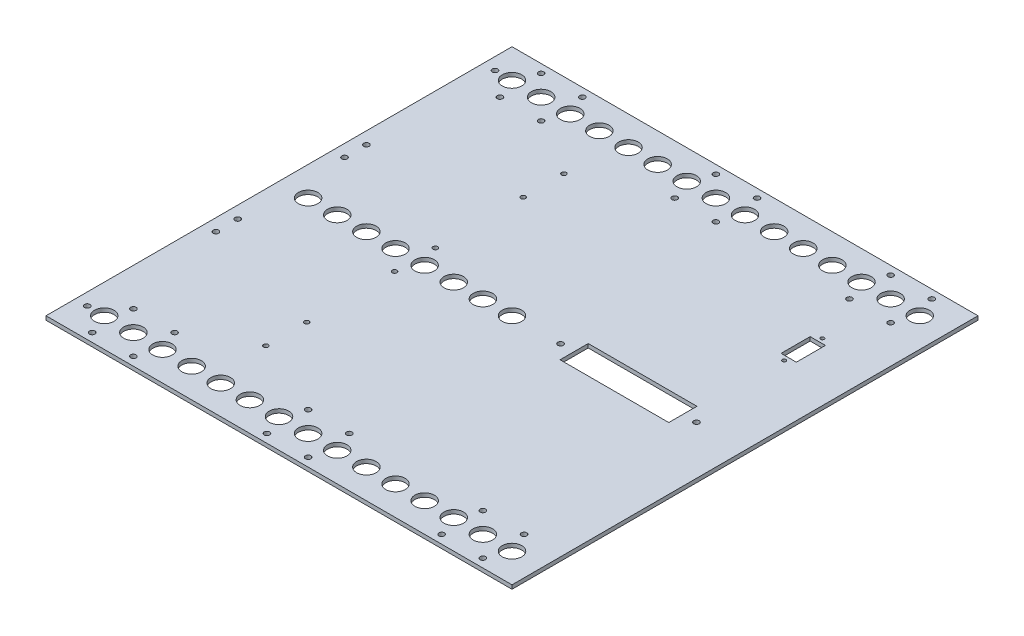
SolidWorks part; units mm, degrees
ref_plane "Front Plane" through (0, 0, 0) normal (0, 0, 1) x (1, 0, 0)
ref_plane "Top Plane" through (0, 0, 0) normal (0, 1, 0) x (1, 0, 0)
ref_plane "Right Plane" through (0, 0, 0) normal (1, 0, 0) x (0, 0, -1)
sketch "Sketch1" plane through (0, 0, 0) normal (0, 1, 0) x (1, 0, 0)
  line L0 (153.4074, 0) -> (-151.3926, 0) construction
  line L1 (-95.25, 133.35) -> (-25.4127, 133.35) construction
  line L2 (-133.35, -133.35) -> (-97.9889, -133.35) construction
  line L3 (-152.4, 42.8625) -> (-136.525, 26.9875) construction
  line L4 (-152.4, 26.9875) -> (-136.525, 42.8625) construction
  line L5 (-152.4, 125.4125) -> (-136.525, 141.2875) construction
  line L6 (-152.4, 141.2875) -> (-136.525, 125.4125) construction
  line L7 (-152.4, 84.1375) -> (-63.5, 84.1375) construction
  line L8 (-63.5, 70.8025) -> (-63.5, 97.4725) construction
  line L9 (-152.4, 141.2875) -> (-152.4, 125.4125) construction
  line L10 (-152.4, 141.2875) -> (-136.525, 141.2875) construction
  line L11 (-136.525, 141.2875) -> (-136.525, 125.4125) construction
  line L12 (-136.525, 125.4125) -> (-12.7, 125.4125) construction
  line L13 (-12.7, 125.4125) -> (-12.7, 42.8625) construction
  line L14 (-12.7, 42.8625) -> (-136.525, 42.8625) construction
  line L15 (-136.525, 42.8625) -> (-136.525, 26.9875) construction
  line L16 (-136.525, 26.9875) -> (-152.4, 26.9875) construction
  line L17 (-152.4, 26.9875) -> (-152.4, 42.8625) construction
  line L18 (-152.4, 125.4125) -> (-152.4, 42.8625) construction
  line L19 (-152.4, -41.275) -> (-136.525, -57.15) construction
  line L20 (-152.4, -152.4) -> (152.4, -152.4)
  line L21 (-152.4, -152.4) -> (-152.4, 152.4)
  line L22 (-152.4, 152.4) -> (152.4, 152.4)
  line L23 (152.4, -152.4) -> (152.4, 152.4)
  line L24 (-152.4, -152.4) -> (152.4, 152.4) construction
  line L25 (-152.4, 152.4) -> (152.4, -152.4) construction
  line L26 (-152.4, -57.15) -> (-136.525, -41.275) construction
  line L27 (-152.4, 41.275) -> (-136.525, 57.15) construction
  line L28 (-152.4, 57.15) -> (-136.525, 41.275) construction
  line L29 (-152.4, 0) -> (-63.5, 0) construction
  line L30 (-63.5, -13.335) -> (-63.5, 13.335) construction
  line L31 (-152.4, 57.15) -> (-152.4, 41.275) construction
  line L32 (-152.4, 57.15) -> (-136.525, 57.15) construction
  line L33 (-136.525, 57.15) -> (-136.525, 41.275) construction
  line L34 (-136.525, 41.275) -> (-12.7, 41.275) construction
  line L35 (-12.7, 41.275) -> (-12.7, -41.275) construction
  line L36 (-12.7, -41.275) -> (-136.525, -41.275) construction
  line L37 (-136.525, -41.275) -> (-136.525, -57.15) construction
  line L38 (-136.525, -57.15) -> (-152.4, -57.15) construction
  line L39 (-152.4, -57.15) -> (-152.4, -41.275) construction
  line L40 (-152.4, 41.275) -> (-152.4, -41.275) construction
  line L41 (-152.4, -125.4125) -> (-136.525, -141.2875) construction
  line L42 (-152.4, -141.2875) -> (-136.525, -125.4125) construction
  line L43 (-152.4, -42.8625) -> (-136.525, -26.9875) construction
  line L44 (-152.4, -26.9875) -> (-136.525, -42.8625) construction
  line L45 (-152.4, -84.1375) -> (-63.5, -84.1375) construction
  line L46 (-63.5, -97.4725) -> (-63.5, -70.8025) construction
  line L47 (-152.4, -26.9875) -> (-152.4, -42.8625) construction
  line L48 (-152.4, -26.9875) -> (-136.525, -26.9875) construction
  line L49 (-136.525, -26.9875) -> (-136.525, -42.8625) construction
  line L50 (-136.525, -42.8625) -> (-12.7, -42.8625) construction
  line L51 (-12.7, -42.8625) -> (-12.7, -125.4125) construction
  line L52 (-12.7, -125.4125) -> (-136.525, -125.4125) construction
  line L53 (-136.525, -125.4125) -> (-136.525, -141.2875) construction
  line L54 (-136.525, -141.2875) -> (-152.4, -141.2875) construction
  line L55 (-152.4, -141.2875) -> (-152.4, -125.4125) construction
  line L56 (-152.4, -42.8625) -> (-152.4, -125.4125) construction
  line L57 (109.3, 66.7) -> (119.3, 85.7) construction
  line L58 (109.3, 85.7) -> (119.3, 85.7)
  line L59 (109.3, 85.7) -> (109.3, 66.7)
  line L60 (109.3, 66.7) -> (119.3, 66.7)
  line L61 (119.3, 85.7) -> (119.3, 66.7)
  line L62 (109.3, 85.7) -> (119.3, 66.7) construction
  line L63 (114.3, 63.7) -> (114.3, 88.7) construction
  line L64 (19.05, -34.925) -> (133.35, 34.925) construction
  line L65 (19.05, 34.925) -> (133.35, 34.925) construction
  line L66 (19.05, 34.925) -> (19.05, -34.925) construction
  line L67 (19.05, -34.925) -> (133.35, -34.925) construction
  line L68 (133.35, 34.925) -> (133.35, -34.925) construction
  line L69 (133.35, 34.925) -> (19.05, 34.925) construction
  line L70 (19.05, 34.925) -> (133.35, -34.925) construction
  line L71 (120.6616, 0) -> (31.7384, 0) construction
  line L72 (40.64, -9.2075) -> (111.76, -9.2075)
  line L73 (40.64, -9.2075) -> (40.64, 9.2075)
  line L74 (40.64, 9.2075) -> (111.76, 9.2075)
  line L75 (111.76, -9.2075) -> (111.76, 9.2075)
  line L76 (40.64, -9.2075) -> (111.76, 9.2075) construction
  line L77 (40.64, 9.2075) -> (111.76, -9.2075) construction
  circle A0 centre (-133.35, 133.35) radius 6.3627
  circle A1 centre (-114.3, 133.35) radius 6.3627
  circle A2 centre (-95.25, 133.35) radius 6.3627
  circle A3 centre (-76.2, 133.35) radius 6.3627
  circle A4 centre (-57.15, 133.35) radius 6.3627
  circle A5 centre (-38.1, 133.35) radius 6.3627
  circle A6 centre (-19.05, 133.35) radius 6.3627
  circle A7 centre (0, 133.35) radius 6.3627
  circle A8 centre (19.05, 133.35) radius 6.3627
  circle A9 centre (38.1, 133.35) radius 6.3627
  circle A10 centre (57.15, 133.35) radius 6.3627
  circle A11 centre (76.2, 133.35) radius 6.3627
  circle A12 centre (95.25, 133.35) radius 6.3627
  circle A13 centre (114.3, 133.35) radius 6.3627
  circle A14 centre (133.35, 133.35) radius 6.3627
  circle A15 centre (-114.3, 0) radius 6.3627
  circle A16 centre (-95.25, 0) radius 6.3627
  circle A17 centre (-76.2, 0) radius 6.3627
  circle A18 centre (-57.15, 0) radius 6.3627
  circle A19 centre (-38.1, 0) radius 6.3627
  circle A20 centre (-19.05, 0) radius 6.3627
  circle A21 centre (0, 0) radius 6.3627
  circle A22 centre (-127.7704, 146.8204) radius 1.778
  circle A23 centre (-100.8296, 146.8204) radius 1.778
  circle A24 centre (-100.8296, 119.8796) radius 1.778
  circle A25 centre (-127.7704, 119.8796) radius 1.778
  circle A26 centre (-13.4704, 146.8204) radius 1.778
  circle A27 centre (13.4704, 146.8204) radius 1.778
  circle A28 centre (-114.3, -133.35) radius 6.3627
  circle A29 centre (-95.25, -133.35) radius 6.3627
  circle A30 centre (-76.2, -133.35) radius 6.3627
  circle A31 centre (-57.15, -133.35) radius 6.3627
  circle A32 centre (-38.1, -133.35) radius 6.3627
  circle A33 centre (-19.05, -133.35) radius 6.3627
  circle A34 centre (0, -133.35) radius 6.3627
  circle A35 centre (19.05, -133.35) radius 6.3627
  circle A36 centre (38.1, -133.35) radius 6.3627
  circle A37 centre (57.15, -133.35) radius 6.3627
  circle A38 centre (76.2, -133.35) radius 6.3627
  circle A39 centre (95.25, -133.35) radius 6.3627
  circle A40 centre (114.3, -133.35) radius 6.3627
  circle A41 centre (133.35, -133.35) radius 6.3627
  circle A42 centre (-133.35, 0) radius 6.3627
  circle A43 centre (-133.35, -133.35) radius 6.3627
  circle A51 centre (13.4704, 119.8796) radius 1.778
  circle A52 centre (-13.4704, 119.8796) radius 1.778
  circle A53 centre (127.7704, 146.8204) radius 1.778
  circle A54 centre (127.7704, 119.8796) radius 1.778
  circle A55 centre (100.8296, 119.8796) radius 1.778
  circle A56 centre (100.8296, 146.8204) radius 1.778
  circle A57 centre (127.7704, -119.8796) radius 1.778
  circle A58 centre (127.7704, -146.8204) radius 1.778
  circle A59 centre (100.8296, -146.8204) radius 1.778
  circle A60 centre (100.8296, -119.8796) radius 1.778
  circle A61 centre (13.4704, -119.8796) radius 1.778
  circle A62 centre (13.4704, -146.8204) radius 1.778
  circle A63 centre (-13.4704, -146.8204) radius 1.778
  circle A64 centre (-13.4704, -119.8796) radius 1.778
  circle A65 centre (-127.7704, -119.8796) radius 1.778
  circle A66 centre (-127.7704, -146.8204) radius 1.778
  circle A67 centre (-100.8296, -146.8204) radius 1.778
  circle A68 centre (-100.8296, -119.8796) radius 1.778
  circle A69 centre (-63.5, 97.4725) radius 1.524
  circle A70 centre (-63.5, 70.8025) radius 1.524
  circle A71 centre (-144.4625, 133.35) radius 1.778
  circle A72 centre (-144.4625, 34.925) radius 1.778
  circle A73 centre (-63.5, 13.335) radius 1.524
  circle A74 centre (-63.5, -13.335) radius 1.524
  circle A75 centre (-144.4625, 49.2125) radius 1.778
  circle A76 centre (-144.4625, -49.2125) radius 1.778
  circle A77 centre (-63.5, -70.8025) radius 1.524
  circle A78 centre (-63.5, -97.4725) radius 1.524
  circle A79 centre (-144.4625, -34.925) radius 1.778
  circle A80 centre (-144.4625, -133.35) radius 1.778
  circle A81 centre (114.3, 88.7) radius 1.1906
  circle A82 centre (114.3, 63.7) radius 1.1906
  circle A83 centre (31.7384, 0) radius 1.778
  circle A84 centre (120.6616, 0) radius 1.778
  point P6 (0, 0)
  point P151 (-63.5, 84.1375)
  point P177 (-63.5, 0)
  point P198 (-63.5, -84.1375)
  point P220 (114.3, 76.2)
  point P226 (76.2, 0)
  point P234 (76.2, 0)
  dimension "D1" = 123.825
  dimension "D2" = 82.55
  dimension "D3" = 15.875
  dimension "D4" = 26.67
  dimension "D5" = 88.9
  dimension "D6" = 123.825
  dimension "D7" = 82.55
  dimension "D8" = 88.9
  dimension "D9" = 26.67
  dimension "D10" = 15.875
  dimension "D11" = 123.825
  dimension "D12" = 82.55
  dimension "D13" = 26.67
  dimension "D14" = 88.9
  dimension "D15" = 15.875
  dimension "D16" = 19
  dimension "D17" = 10
  dimension "D18" = 25
  dimension "D19" = 76.2
  dimension "D20" = 38.1
  dimension "D21" = 114.3
  dimension "D22" = 69.85
  dimension "D23" = 71.12
  dimension "D24" = 18.415
  dimension "D25" = 88.9231
  dimension "D26" = 19.05
extrude "Boss-Extrude1" add sketch "Sketch1" along normal blind 2.54
